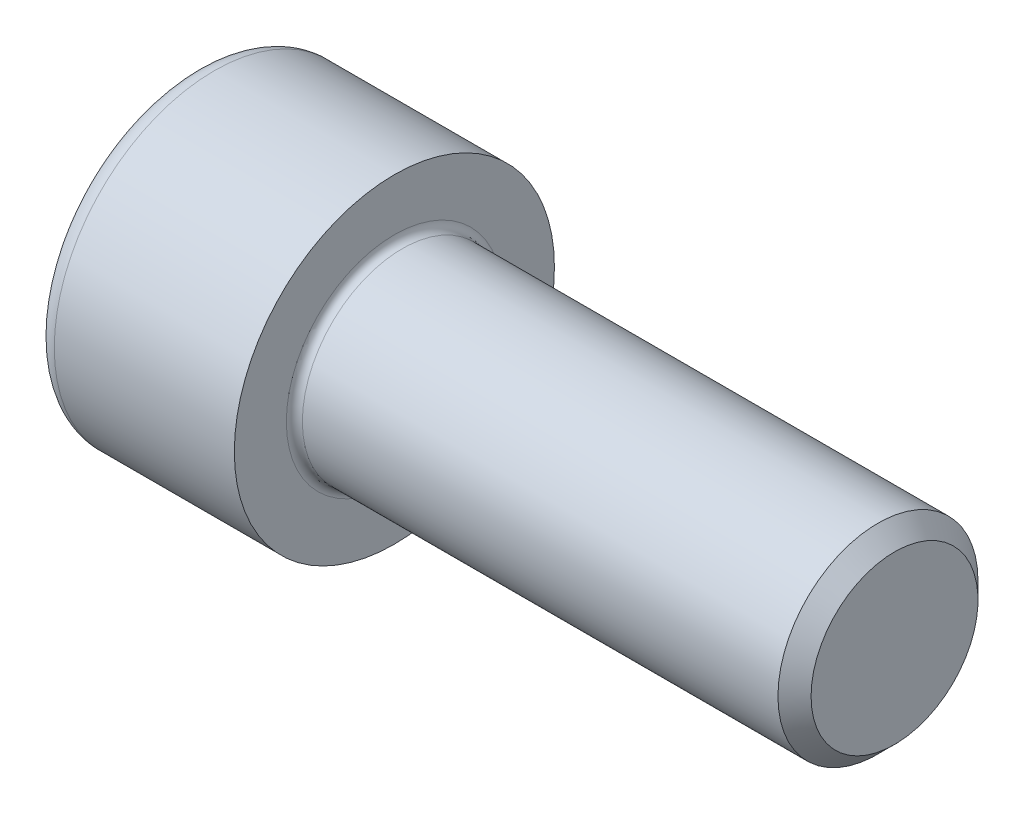
SolidWorks part; units mm, degrees
revolve "Base-Revolve" add sketch "BodySke"
sketch "BodySke" plane through (0, 0, 0) normal (0, 0, 1) x (1, 0, 0)
  line L0 (0, 0) -> (0, 8)
  line L1 (0, 8) -> (10, 8)
  line L2 (10, 8) -> (10, 5)
  line L3 (10, 5) -> (34.172, 5)
  line L4 (35, 4.172) -> (35, 0)
  line L5 (35, 0) -> (0, 0)
  line L6 (-31.75, 0) -> (127, 0) construction
  line L8 (35, 4.172) -> (34.172, 5)
  line L10 (35, -4.172) -> (34.172, -5) construction
  line L11 (11.5, 9.525) -> (11.5, 3.175) construction
  line L12 (10, 9.525) -> (10, 3.175) construction
  line L13 (-25, 9.525) -> (-25, 3.175) construction
  dimension "Head_ht" = 10
  dimension "Length" = 25
  dimension "Body_ch_ang" = 45
  dimension "Diameter" = 10
  dimension "Minor_dia" = 8.344
  dimension "Advance" = 1.5
  dimension "Thread_nom" = 25
  dimension "Thread_length" = 60
  dimension "Head_dia" = 16
cosmetic thread "ThreadCosmetic" [suppressed]
fillet "Fillet1" radius 0.4 1 edges at (10, 0, 5)
fillet "Fillet2" radius 1 1 edges at (0, 0, 8)
ref_plane "Plane1" through (0, 0, 0) normal (0, 0, 1) x (1, 0, 0)
ref_plane "Plane2" through (0, 0, 0) normal (0, 1, 0) x (1, 0, 0)
ref_plane "Plane3" through (0, 0, 0) normal (1, 0, 0) x (0, 0, -1)
sketch "Sketch2" plane through (0, 0, 0) normal (0, 0, 1) x (1, 0, 0)
  line L0 (0, 4.0125) -> (5, 4.0125)
  line L1 (5, 4.0125) -> (7.3166, 0)
  line L2 (-31.75, 0) -> (127, 0) construction
  line L3 (7.3166, 0) -> (0, 0)
  line L4 (0, 0) -> (0, 4.0125)
  line L6 (0, 0) -> (47.625, 0) construction
  dimension "D1" = 4.0125
  dimension "D2" = 60
  dimension "Depth" = 5
revolve "Hex-PreBroach" cut sketch "Sketch2" angle 360 about L6
sketch "Sketch3" plane through (0, 0, 0) normal (-1, 0, 0) x (0, 0.5, 0.866)
  line L0 (2.3166, 4.0125) -> (-2.3166, 4.0125)
  line L1 (-2.3166, 4.0125) -> (-4.6332, 0)
  line L2 (2.3166, 4.0125) -> (4.6332, 0)
  line L3 (2.3166, -4.0125) -> (4.6332, 0)
  line L4 (2.3166, -4.0125) -> (-2.3166, -4.0125)
  line L5 (-2.3166, -4.0125) -> (-4.6332, 0)
  dimension "D1" = 4.0125
  dimension "D2" = 4.0125
  dimension "Hex_size" = 8.025
extrude "Hex" cut sketch "Sketch3" against normal blind 5
sketch "ThdSchSke" plane through (0, 0, 0) normal (0, 0, 1) x (1, 0, 0)
  line L0 (14.5, -4.172) -> (13.9202, -5)
  line L1 (14.5, -4.172) -> (15.0798, -5)
  line L2 (15.0798, -5) -> (15.0798, -6.25)
  line L3 (-3.175, 0) -> (5.1513, 0) construction
  line L4 (0, 7) -> (0, -7) construction
  line L5 (15.0798, -6.25) -> (13.9202, -6.25)
  line L6 (13.9202, -6.25) -> (13.9202, -5)
  dimension "Thread_minor" = 8.344
  dimension "Diameter" = 10
  dimension "Start" = 14.5
revolve "ThreadSchematic" [suppressed] cut sketch "ThdSchSke" angle 360 about L3
pattern_linear "ThdSchPat" [suppressed]
equation "\"D2@Sketch3\" = \"Hex_size@Sketch3\" / 2"
equation "\"D1@Sketch3\" = \"Hex_size@Sketch3\" / 2"
equation "\"D1@Sketch2\" = \"Hex_size@Sketch3\" / 2"
equation "\"Thread_minor@ThreadCosmetic\"  =  \"Minor_dia@BodySke\""
equation "\"Depth@Sketch2\" =  \"Key_eng@Hex\""
equation "\"Thread_length@ThreadCosmetic\" = ((sgn( (\"Length@BodySke\" - \"Advance@BodySke\" * 3.0) - \"Thread_nom@BodySke\" )-1)*( (\"Length@BodySke\" - \"Advance@BodySke\" * 3.0) - \"Thread_nom@BodySke\" ))/-2+ \"Thread_nom@BodySke\""
equation "\"Thread_minor@ThdSchSke\" = \"Minor_dia@BodySke\""
equation "\"Diameter@ThdSchSke\" = \"Diameter@BodySke\""
equation "\"Overcut@ThdSchSke\" = \"Diameter@BodySke\" * 1.25"
equation "\"Start@ThdSchSke\" = \"Head_ht@BodySke\" + \"Length@BodySke\" - \"Thread_length@ThreadCosmetic\"  '---Non-countersunk---"
equation "\"Num_threads@ThdSchPat\" = int( \"Thread_length@ThreadCosmetic\" / \"Advance@BodySke\" + 0.999 )  + 1"
equation "\"Advance@ThdSchPat\" = \"Thread_length@ThreadCosmetic\" /  (\"Num_threads@ThdSchPat\" - 1) 'relax it"
equation "\"Num_threads@ThdSchPat\" = \"Num_threads@ThdSchPat\" - sgn( \"Num_threads@ThdSchPat\" - 1) '---chamfered tips only---"
